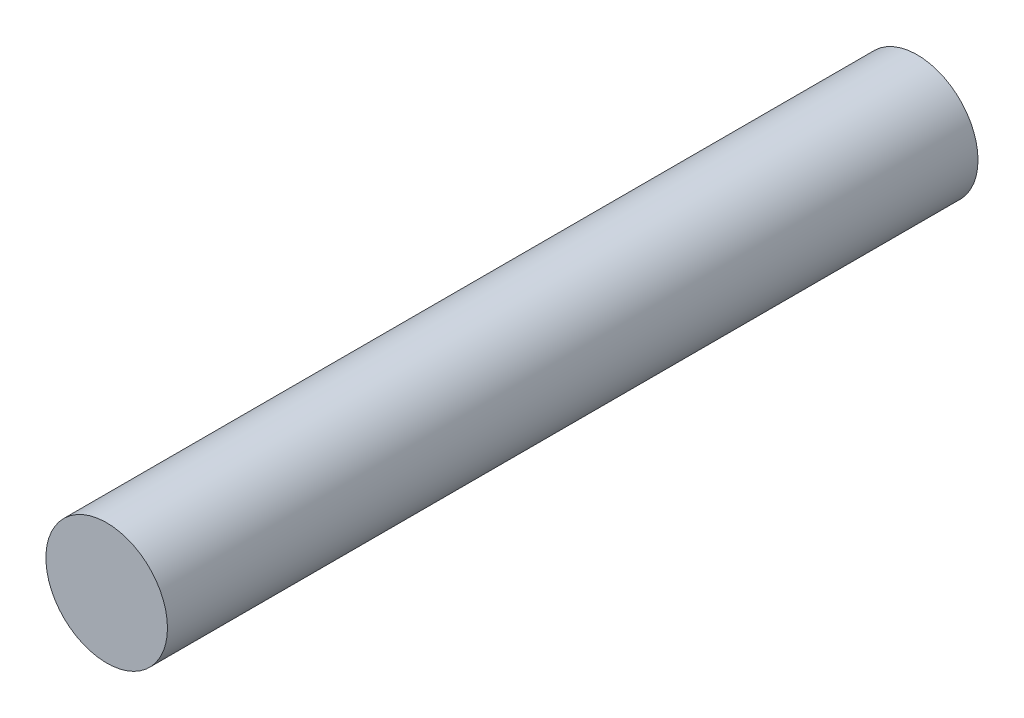
SolidWorks part; units mm, degrees
ref_plane "Plan de face" through (0, 0, 0) normal (0, 0, 1) x (1, 0, 0)
ref_plane "Plan de dessus" through (0, 0, 0) normal (0, 1, 0) x (1, 0, 0)
ref_plane "Plan de droite" through (0, 0, 0) normal (1, 0, 0) x (0, 0, -1)
sketch "Esquisse1" plane through (0, 0, 0) normal (0, 0, 1) x (1, 0, 0)
  circle A0 centre (0, 0) radius 1.5
  dimension "D1" = 3
extrude "Boss.-Extru.1" add sketch "Esquisse1" along normal mid plane 20
